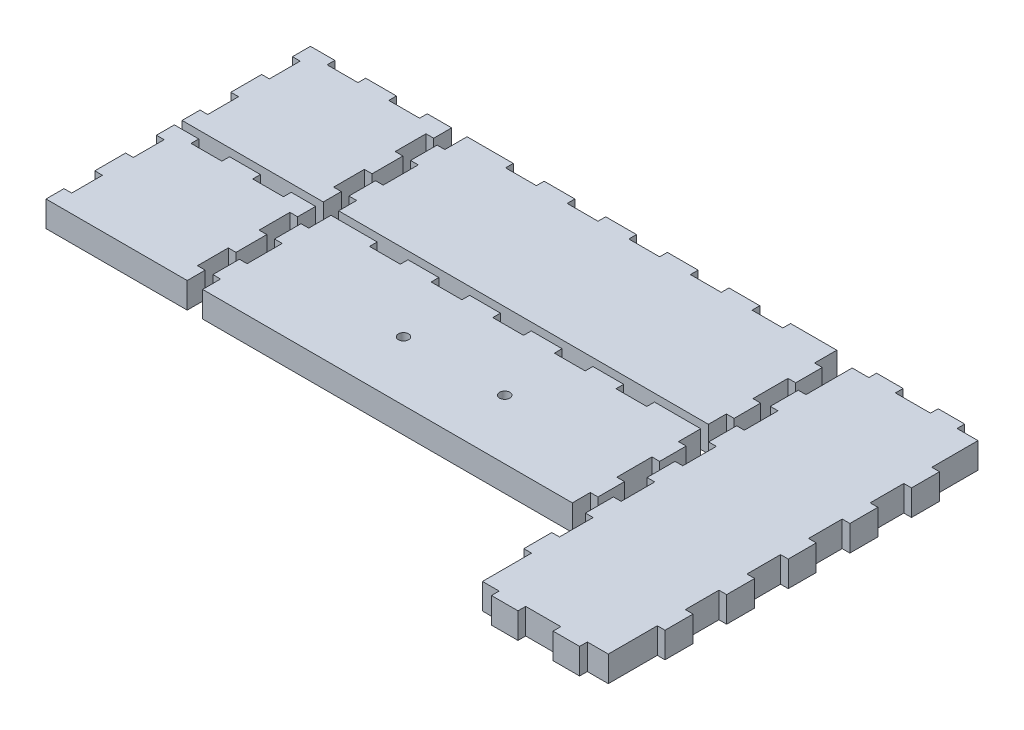
SolidWorks part; units mm, degrees
ref_plane "Front Plane" through (0, 0, 0) normal (0, 0, 1) x (1, 0, 0)
ref_plane "Top Plane" through (0, 0, 0) normal (0, 1, 0) x (1, 0, 0)
ref_plane "Right Plane" through (0, 0, 0) normal (1, 0, 0) x (0, 0, -1)
sketch "Sketch1" plane through (0, 0, 0) normal (0, 1, 0) x (1, 0, 0)
  line L22 (-32.8129, 122.7037) -> (-20.8129, 122.7037)
  line L30 (-135.8129, 125.7037) -> (-126.3129, 125.7037)
  line L31 (-135.8129, 125.7037) -> (-135.8129, 122.7037)
  line L33 (-126.3129, 125.7037) -> (-126.3129, 122.7037)
  line L34 (-126.3129, 122.7037) -> (-114.3129, 122.7037)
  line L35 (-135.8129, 122.7037) -> (-135.8129, 118.7037)
  line L36 (-135.8129, 118.7037) -> (-132.8129, 118.7037)
  line L37 (-80.8129, 122.7037) -> (-80.8129, 118.7037)
  line L39 (-83.8129, 118.7037) -> (-80.8129, 118.7037)
  line L40 (-114.3129, 125.7037) -> (-102.3129, 125.7037)
  line L41 (-114.3129, 125.7037) -> (-114.3129, 122.7037)
  line L43 (-102.3129, 125.7037) -> (-102.3129, 122.7037)
  line L44 (-90.3129, 125.7037) -> (-80.8129, 125.7037)
  line L45 (-90.3129, 125.7037) -> (-90.3129, 122.7037)
  line L47 (-80.8129, 125.7037) -> (-80.8129, 122.7037)
  line L49 (-132.8129, 118.7037) -> (-132.8129, 106.7037)
  line L51 (-83.8129, 118.7037) -> (-83.8129, 106.7037)
  line L52 (-135.8129, 106.7037) -> (-132.8129, 106.7037)
  line L53 (-135.8129, 106.7037) -> (-135.8129, 94.7037)
  line L54 (-135.8129, 94.7037) -> (-132.8129, 94.7037)
  line L55 (-80.8129, 106.7037) -> (-80.8129, 94.7037)
  line L57 (-132.8129, 94.7037) -> (-132.8129, 82.7037)
  line L59 (-83.8129, 94.7037) -> (-83.8129, 82.7037)
  line L60 (-135.8129, 82.7037) -> (-132.8129, 82.7037)
  line L61 (-135.8129, 82.7037) -> (-135.8129, 75.7037)
  line L62 (-135.8129, 75.7037) -> (-80.8129, 75.7037)
  line L63 (-80.8129, 82.7037) -> (-80.8129, 75.7037)
  line L64 (-83.8129, 106.7037) -> (-80.8129, 106.7037)
  line L65 (-83.8129, 94.7037) -> (-80.8129, 94.7037)
  line L66 (-83.8129, 82.7037) -> (-80.8129, 82.7037)
  line L67 (-102.3129, 122.7037) -> (-90.3129, 122.7037)
  line L68 (69.1871, 117.0367) -> (72.1871, 117.0367)
  line L69 (-74.8129, 125.7037) -> (-56.8129, 125.7037)
  line L70 (-74.8129, 125.7037) -> (-74.8129, 122.7037)
  line L72 (-56.8129, 125.7037) -> (-56.8129, 122.7037)
  line L73 (-56.8129, 122.7037) -> (-44.8129, 122.7037)
  line L74 (-74.8129, 122.7037) -> (-74.8129, 117.0367)
  line L76 (69.1871, 122.7037) -> (69.1871, 117.0367)
  line L77 (-77.8129, 117.0367) -> (-74.8129, 117.0367)
  line L78 (-77.8129, 117.0367) -> (-77.8129, 106.7037)
  line L79 (-77.8129, 106.7037) -> (-74.8129, 106.7037)
  line L80 (72.1871, 117.0367) -> (72.1871, 106.7037)
  line L82 (-74.8129, 106.7037) -> (-74.8129, 93.0367)
  line L84 (69.1871, 106.7037) -> (69.1871, 93.0367)
  line L85 (-77.8129, 93.0367) -> (-74.8129, 93.0367)
  line L86 (-77.8129, 93.0367) -> (-77.8129, 82.7037)
  line L87 (-77.8129, 82.7037) -> (-74.8129, 82.7037)
  line L88 (72.1871, 93.0367) -> (72.1871, 82.7037)
  line L90 (-74.8129, 82.7037) -> (-74.8129, 75.7037)
  line L91 (-74.8129, 75.7037) -> (69.1871, 75.7037)
  line L92 (69.1871, 82.7037) -> (69.1871, 75.7037)
  line L93 (-44.8129, 125.7037) -> (-32.8129, 125.7037)
  line L94 (-44.8129, 125.7037) -> (-44.8129, 122.7037)
  line L96 (-32.8129, 125.7037) -> (-32.8129, 122.7037)
  line L97 (-20.8129, 125.7037) -> (-8.8129, 125.7037)
  line L98 (-20.8129, 125.7037) -> (-20.8129, 122.7037)
  line L100 (-8.8129, 125.7037) -> (-8.8129, 122.7037)
  line L101 (3.1871, 125.7037) -> (15.1871, 125.7037)
  line L102 (3.1871, 125.7037) -> (3.1871, 122.7037)
  line L104 (15.1871, 125.7037) -> (15.1871, 122.7037)
  line L105 (27.1871, 125.7037) -> (39.1871, 125.7037)
  line L106 (27.1871, 125.7037) -> (27.1871, 122.7037)
  line L108 (39.1871, 125.7037) -> (39.1871, 122.7037)
  line L109 (51.1871, 125.7037) -> (69.1871, 125.7037)
  line L110 (51.1871, 125.7037) -> (51.1871, 122.7037)
  line L112 (69.1871, 125.7037) -> (69.1871, 122.7037)
  line L113 (69.1871, 106.7037) -> (72.1871, 106.7037)
  line L114 (69.1871, 93.0367) -> (72.1871, 93.0367)
  line L115 (69.1871, 82.7037) -> (72.1871, 82.7037)
  line L116 (-8.8129, 122.7037) -> (3.1871, 122.7037)
  line L117 (15.1871, 122.7037) -> (27.1871, 122.7037)
  line L118 (39.1871, 122.7037) -> (51.1871, 122.7037)
  line L119 (-135.8129, 72.7037) -> (-126.3129, 72.7037)
  line L120 (-135.8129, 72.7037) -> (-135.8129, 69.7037)
  line L121 (-126.3129, 72.7037) -> (-126.3129, 69.7037)
  line L122 (-126.3129, 69.7037) -> (-114.3129, 69.7037)
  line L123 (-135.8129, 69.7037) -> (-135.8129, 65.7037)
  line L124 (-135.8129, 65.7037) -> (-132.8129, 65.7037)
  line L125 (-80.8129, 69.7037) -> (-80.8129, 65.7037)
  line L126 (-83.8129, 65.7037) -> (-80.8129, 65.7037)
  line L127 (-114.3129, 72.7037) -> (-102.3129, 72.7037)
  line L128 (-114.3129, 72.7037) -> (-114.3129, 69.7037)
  line L129 (-102.3129, 72.7037) -> (-102.3129, 69.7037)
  line L130 (-90.3129, 72.7037) -> (-80.8129, 72.7037)
  line L131 (-90.3129, 72.7037) -> (-90.3129, 69.7037)
  line L132 (-80.8129, 72.7037) -> (-80.8129, 69.7037)
  line L133 (-132.8129, 65.7037) -> (-132.8129, 53.7037)
  line L134 (-83.8129, 65.7037) -> (-83.8129, 53.7037)
  line L135 (-135.8129, 53.7037) -> (-132.8129, 53.7037)
  line L136 (-135.8129, 53.7037) -> (-135.8129, 41.7037)
  line L137 (-135.8129, 41.7037) -> (-132.8129, 41.7037)
  line L138 (-80.8129, 53.7037) -> (-80.8129, 41.7037)
  line L139 (-132.8129, 41.7037) -> (-132.8129, 29.7037)
  line L140 (-83.8129, 41.7037) -> (-83.8129, 29.7037)
  line L141 (-135.8129, 29.7037) -> (-132.8129, 29.7037)
  line L142 (-135.8129, 29.7037) -> (-135.8129, 22.7037)
  line L143 (-135.8129, 22.7037) -> (-80.8129, 22.7037)
  line L144 (-80.8129, 29.7037) -> (-80.8129, 22.7037)
  line L145 (-83.8129, 53.7037) -> (-80.8129, 53.7037)
  line L146 (-83.8129, 41.7037) -> (-80.8129, 41.7037)
  line L147 (-83.8129, 29.7037) -> (-80.8129, 29.7037)
  line L148 (-102.3129, 69.7037) -> (-90.3129, 69.7037)
  line L149 (-32.8129, 69.7037) -> (-20.8129, 69.7037)
  line L150 (69.1871, 64.0367) -> (72.1871, 64.0367)
  line L151 (-74.8129, 72.7037) -> (-56.8129, 72.7037)
  line L152 (-74.8129, 72.7037) -> (-74.8129, 69.7037)
  line L153 (-56.8129, 72.7037) -> (-56.8129, 69.7037)
  line L154 (-56.8129, 69.7037) -> (-44.8129, 69.7037)
  line L155 (-74.8129, 69.7037) -> (-74.8129, 64.0367)
  line L156 (69.1871, 69.7037) -> (69.1871, 64.0367)
  line L157 (-77.8129, 64.0367) -> (-74.8129, 64.0367)
  line L158 (-77.8129, 64.0367) -> (-77.8129, 53.7037)
  line L159 (-77.8129, 53.7037) -> (-74.8129, 53.7037)
  line L160 (72.1871, 64.0367) -> (72.1871, 53.7037)
  line L161 (-74.8129, 53.7037) -> (-74.8129, 40.0367)
  line L162 (69.1871, 53.7037) -> (69.1871, 40.0367)
  line L163 (-77.8129, 40.0367) -> (-74.8129, 40.0367)
  line L164 (-77.8129, 40.0367) -> (-77.8129, 29.7037)
  line L165 (-77.8129, 29.7037) -> (-74.8129, 29.7037)
  line L166 (72.1871, 40.0367) -> (72.1871, 29.7037)
  line L167 (-74.8129, 29.7037) -> (-74.8129, 22.7037)
  line L168 (-74.8129, 22.7037) -> (69.1871, 22.7037)
  line L169 (69.1871, 29.7037) -> (69.1871, 22.7037)
  line L170 (-44.8129, 72.7037) -> (-32.8129, 72.7037)
  line L171 (-44.8129, 72.7037) -> (-44.8129, 69.7037)
  line L172 (-32.8129, 72.7037) -> (-32.8129, 69.7037)
  line L173 (-20.8129, 72.7037) -> (-8.8129, 72.7037)
  line L174 (-20.8129, 72.7037) -> (-20.8129, 69.7037)
  line L175 (-8.8129, 72.7037) -> (-8.8129, 69.7037)
  line L176 (3.1871, 72.7037) -> (15.1871, 72.7037)
  line L177 (3.1871, 72.7037) -> (3.1871, 69.7037)
  line L178 (15.1871, 72.7037) -> (15.1871, 69.7037)
  line L179 (27.1871, 72.7037) -> (39.1871, 72.7037)
  line L180 (27.1871, 72.7037) -> (27.1871, 69.7037)
  line L181 (39.1871, 72.7037) -> (39.1871, 69.7037)
  line L182 (51.1871, 72.7037) -> (69.1871, 72.7037)
  line L183 (51.1871, 72.7037) -> (51.1871, 69.7037)
  line L184 (69.1871, 72.7037) -> (69.1871, 69.7037)
  line L185 (69.1871, 53.7037) -> (72.1871, 53.7037)
  line L186 (69.1871, 40.0367) -> (72.1871, 40.0367)
  line L187 (69.1871, 29.7037) -> (72.1871, 29.7037)
  line L188 (-8.8129, 69.7037) -> (3.1871, 69.7037)
  line L189 (15.1871, 69.7037) -> (27.1871, 69.7037)
  line L190 (39.1871, 69.7037) -> (51.1871, 69.7037)
  line L191 (95.0219, 122.7037) -> (108.6871, 122.7037)
  line L192 (84.6871, 125.7037) -> (95.0219, 125.7037)
  line L193 (84.6871, 125.7037) -> (84.6871, 122.7037)
  line L194 (84.6871, -24.2963) -> (95.0219, -24.2963)
  line L195 (95.0219, 125.7037) -> (95.0219, 122.7037)
  line L196 (108.6871, 125.7037) -> (119.0219, 125.7037)
  line L197 (108.6871, 125.7037) -> (108.6871, 122.7037)
  line L198 (108.6871, -24.2963) -> (119.0219, -24.2963)
  line L199 (119.0219, 125.7037) -> (119.0219, 122.7037)
  line L201 (78.1871, -2.201) -> (78.1871, -21.2963)
  line L202 (78.1871, -21.2963) -> (84.6871, -21.2963)
  line L203 (127.1871, -2.201) -> (127.1871, -21.2963)
  line L204 (75.1871, 8.7037) -> (78.1871, 8.7037)
  line L205 (75.1871, 8.7037) -> (75.1871, -2.201)
  line L206 (75.1871, -2.201) -> (78.1871, -2.201)
  line L207 (130.1871, 8.7037) -> (130.1871, -2.201)
  line L209 (78.1871, 21.799) -> (78.1871, 8.7037)
  line L211 (127.1871, 21.799) -> (127.1871, 8.7037)
  line L212 (75.1871, 32.7037) -> (78.1871, 32.7037)
  line L213 (75.1871, 32.7037) -> (75.1871, 21.799)
  line L214 (75.1871, 21.799) -> (78.1871, 21.799)
  line L215 (130.1871, 32.7037) -> (130.1871, 21.799)
  line L217 (78.1871, 45.799) -> (78.1871, 32.7037)
  line L219 (127.1871, 45.799) -> (127.1871, 32.7037)
  line L220 (75.1871, 56.7037) -> (78.1871, 56.7037)
  line L221 (75.1871, 56.7037) -> (75.1871, 45.799)
  line L222 (75.1871, 45.799) -> (78.1871, 45.799)
  line L223 (130.1871, 56.7037) -> (130.1871, 45.799)
  line L225 (78.1871, 69.799) -> (78.1871, 56.7037)
  line L227 (127.1871, 69.799) -> (127.1871, 56.7037)
  line L228 (75.1871, 80.7037) -> (78.1871, 80.7037)
  line L229 (75.1871, 80.7037) -> (75.1871, 69.799)
  line L230 (75.1871, 69.799) -> (78.1871, 69.799)
  line L231 (130.1871, 80.7037) -> (130.1871, 69.799)
  line L233 (78.1871, 80.7037) -> (78.1871, 93.799)
  line L235 (127.1871, 80.7037) -> (127.1871, 93.799)
  line L236 (130.1871, 104.7037) -> (127.1871, 104.7037)
  line L237 (130.1871, 104.7037) -> (130.1871, 93.799)
  line L238 (130.1871, 93.799) -> (127.1871, 93.799)
  line L239 (75.1871, 104.7037) -> (75.1871, 93.799)
  line L240 (78.1871, 122.7037) -> (84.6871, 122.7037)
  line L241 (78.1871, 122.7037) -> (78.1871, 104.7037)
  line L243 (127.1871, 122.7037) -> (127.1871, 104.7037)
  line L244 (84.6871, -21.2963) -> (84.6871, -24.2963)
  line L245 (95.0219, -21.2963) -> (95.0219, -24.2963)
  line L246 (108.6871, -21.2963) -> (108.6871, -24.2963)
  line L247 (119.0219, 122.7037) -> (127.1871, 122.7037)
  line L248 (119.0219, -21.2963) -> (119.0219, -24.2963)
  line L249 (78.1871, 104.7037) -> (75.1871, 104.7037)
  line L250 (127.1871, 69.799) -> (130.1871, 69.799)
  line L251 (78.1871, 93.799) -> (75.1871, 93.799)
  line L252 (127.1871, 80.7037) -> (130.1871, 80.7037)
  line L253 (127.1871, 56.7037) -> (130.1871, 56.7037)
  line L254 (127.1871, 45.799) -> (130.1871, 45.799)
  line L255 (127.1871, 32.7037) -> (130.1871, 32.7037)
  line L256 (127.1871, 21.799) -> (130.1871, 21.799)
  line L257 (127.1871, 8.7037) -> (130.1871, 8.7037)
  line L259 (127.1871, -2.201) -> (130.1871, -2.201)
  line L260 (95.0219, -21.2963) -> (108.6871, -21.2963)
  line L261 (119.0219, -21.2963) -> (127.1871, -21.2963)
  point P13 (0, 0)
  point P15 (0, 0)
  point P17 (0, 0)
  point P19 (0, 0)
  point P262 (0, 0)
  point P264 (0, 0)
  point P266 (0, 0)
  point P270 (0, 0)
  point P271 (0, 0)
  point P272 (0, 0)
  point P273 (0, 0)
  point P274 (0, 0)
  point P275 (0, 0)
  point P276 (0, 0)
  point P277 (0, 0)
  point P278 (0, 0)
  point P279 (0, 0)
  point P280 (0, 0)
  point P281 (0, 0)
  point P282 (0, 0)
  point P283 (0, 0)
  point P284 (0, 0)
  point P285 (0, 0)
  point P286 (0, 0)
  point P287 (0, 0)
  point P288 (0, 0)
  point P289 (0, 0)
  point P290 (0, 0)
  point P291 (0, 0)
  point P292 (0, 0)
  point P293 (0, 0)
  point P294 (0, 0)
  point P295 (0, 0)
  point P296 (0, 0)
  point P297 (0, 0)
  point P298 (0, 0)
  point P299 (0, 0)
  point P300 (0, 0)
  point P301 (0, 0)
  point P302 (0, 0)
  point P303 (0, 0)
  point P304 (0, 0)
extrude "Boss-Extrude1" add sketch "Sketch1" along normal blind 10 separate body
sketch "Sketch2" plane through (0, 10, 0) normal (0, 1, 0) x (1, 0, 0)
  circle A0 centre (-19.7044, 45.8373) radius 1.9978
  circle A1 centre (19.7066, 45.8414) radius 2
extrude "Cut-Extrude1" cut sketch "Sketch2" against normal through all
